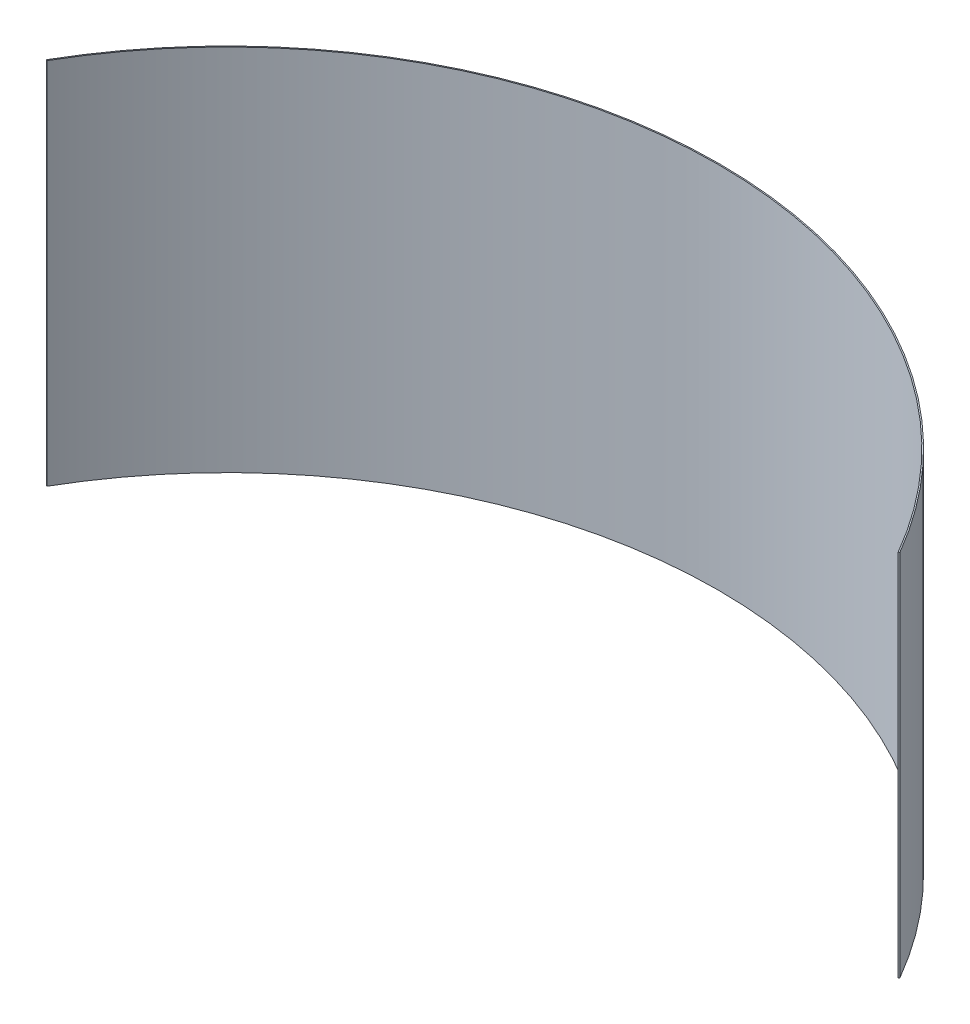
SolidWorks part; units mm, degrees
ref_plane "Ön Düzlem" through (0, 0, 0) normal (0, 0, 1) x (1, 0, 0)
ref_plane "Üst Düzlem" through (0, 0, 0) normal (0, 1, 0) x (1, 0, 0)
ref_plane "Sağ Düzlem" through (0, 0, 0) normal (1, 0, 0) x (0, 0, -1)
sketch "Çizim1" plane through (0, 0, 0) normal (0, 1, 0) x (1, 0, 0)
  line L0 (0, 0) -> (-75.1047, 43.3617) construction
  line L1 (0, 0) -> (77.8313, 44.9359) construction
  line L2 (0, 0) -> (0, 20) construction
  line L3 (17.3205, 10) -> (17.3638, 10.025)
  line L4 (-17.3205, 10) -> (-17.3638, 10.025)
  arc A0 (17.3205, 10) -> (-17.3205, 10) centre (0, 0) ccw
  arc A1 (17.3638, 10.025) -> (-17.3638, 10.025) centre (0, 0) ccw
  dimension "D3" = 20
  dimension "D1" = 60
  dimension "D2" = 60
  dimension "D4" = 0.05
extrude "Yükseklik-Ekstrüzyon1" add sketch "Çizim1" along normal blind 15
